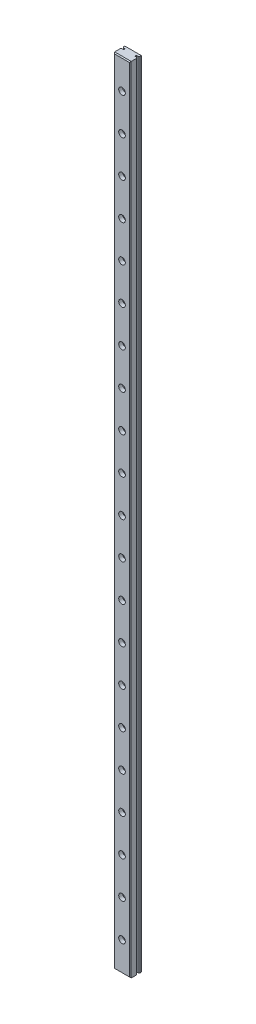
SolidWorks part; units mm, degrees
ref_plane "Alzado" through (0, 0, 0) normal (0, 0, 1) x (1, 0, 0)
ref_plane "Planta" through (0, 0, 0) normal (0, 1, 0) x (1, 0, 0)
ref_plane "Vista lateral" through (0, 0, 0) normal (1, 0, 0) x (0, 0, -1)
sketch "Croquis1" plane through (0, 0, 0) normal (0, 1, 0) x (1, 0, 0)
  line L1 (0, 0) -> (9, 0)
  line L2 (0, 0) -> (0, 6.5)
  line L3 (0, 6.5) -> (9, 6.5)
  line L4 (9, 0) -> (9, 6.5)
  dimension "D1" = 9
  dimension "D2" = 6.5
extrude "Saliente-Extruir1" add sketch "Croquis1" along normal blind 431
sketch "Croquis2" plane through (0, 431, 0) normal (0, 1, 0) x (1, 0, 0)
  line L0 (0, 4) -> (9, 4) construction
  line L1 (0, 6.5) -> (0, 0) construction
  line L2 (9, 0) -> (9, 6.5) construction
  line L3 (4.5, 6.5) -> (4.5, 0) construction
  line L4 (0, 4) -> (1.5, 4)
  line L5 (0, 4) -> (0, 4.75)
  line L6 (0, 4.75) -> (1.5, 4.75)
  line L7 (1.5, 4) -> (1.5, 4.75)
  line L8 (9, 6.5) -> (0, 6.5) construction
  line L9 (0, 0) -> (9, 0) construction
  line L10 (9, 4) -> (9, 4.75)
  line L11 (9, 4) -> (7.5, 4)
  line L12 (7.5, 4) -> (7.5, 4.75)
  line L13 (9, 4.75) -> (7.5, 4.75)
  dimension "D1" = 4
  dimension "D2" = 0.75
  dimension "D3" = 1.5
extrude "Cortar-Extruir1" cut sketch "Croquis2" against normal up to surface (431 mm away) up to face at (4.5, 0, -3.25)
chamfer "Chaflán2" distance 0.5 angle 45 4 edges at (9, 215.5, -4.75) (9, 215.5, -4) (0, 215.5, -4.75) (0, 215.5, -4)
sketch "Croquis3" plane through (0, 0, 0) normal (0, 0, 1) x (1, 0, 0)
  line L0 (4.5, 431) -> (4.5, 0) construction
  line L1 (0, 431) -> (9, 431) construction
  line L2 (0, 0) -> (9, 0) construction
  circle A0 centre (4.5, 415) radius 1.8
  circle A1 centre (4.5, 395) radius 1.8
  circle A2 centre (4.5, 375.0526) radius 1.8
  circle A3 centre (4.5, 355.1053) radius 1.8
  circle A4 centre (4.5, 335.1579) radius 1.8
  circle A5 centre (4.5, 315.2105) radius 1.8
  circle A6 centre (4.5, 295.2632) radius 1.8
  circle A7 centre (4.5, 275.3158) radius 1.8
  circle A8 centre (4.5, 255.3684) radius 1.8
  circle A9 centre (4.5, 235.4211) radius 1.8
  circle A10 centre (4.5, 215.4737) radius 1.8
  circle A11 centre (4.5, 195.5263) radius 1.8
  circle A12 centre (4.5, 175.5789) radius 1.8
  circle A13 centre (4.5, 155.6316) radius 1.8
  circle A14 centre (4.5, 135.6842) radius 1.8
  circle A15 centre (4.5, 115.7368) radius 1.8
  circle A16 centre (4.5, 95.7895) radius 1.8
  circle A17 centre (4.5, 75.8421) radius 1.8
  circle A18 centre (4.5, 55.8947) radius 1.8
  circle A19 centre (4.5, 35.9474) radius 1.8
  circle A20 centre (4.5, 16) radius 1.8
  dimension "D1" = 3.6
  dimension "D3" = 3.6
  dimension "D2" = 16
  dimension "D4" = 20
  dimension "D6" = 16
  dimension "D5" = 20
extrude "Cortar-Extruir2" cut sketch "Croquis3" against normal blind 440
chamfer "Chaflán4" distance 0.5 angle 45 8 edges at (4.5, 431, 0) (9, 215.5, 0) (0, 215.5, 0) (4.5, 0, 0) (4.5, 431, -6.5) (9, 215.5, -6.5) (4.5, 0, -6.5) (0, 215.5, -6.5)
sketch "Croquis4" plane through (0, 0, -6.5) normal (0, 0, -1) x (-1, 0, 0)
  circle A0 centre (-4.5, 415) radius 2.85
  circle A1 centre (-4.5, 395.05) radius 2.85
  circle A2 centre (-4.5, 375.1) radius 2.85
  circle A3 centre (-4.5, 355.15) radius 2.85
  circle A4 centre (-4.5, 335.2) radius 2.85
  circle A5 centre (-4.5, 315.25) radius 2.85
  circle A6 centre (-4.5, 295.3) radius 2.85
  circle A7 centre (-4.5, 275.35) radius 2.85
  circle A8 centre (-4.5, 255.4) radius 2.85
  circle A9 centre (-4.5, 235.45) radius 2.85
  circle A10 centre (-4.5, 215.5) radius 2.85
  circle A11 centre (-4.5, 195.55) radius 2.85
  circle A12 centre (-4.5, 175.6) radius 2.85
  circle A13 centre (-4.5, 155.65) radius 2.85
  circle A14 centre (-4.5, 135.7) radius 2.85
  circle A15 centre (-4.5, 115.75) radius 2.85
  circle A16 centre (-4.5, 95.8) radius 2.85
  circle A17 centre (-4.5, 75.85) radius 2.85
  circle A18 centre (-4.5, 55.9) radius 2.85
  circle A19 centre (-4.5, 35.95) radius 2.85
  circle A20 centre (-4.5, 16) radius 2.85
  dimension "D1" = 5.7
  dimension "D2" = 21
extrude "Cortar-Extruir3" cut sketch "Croquis4" against normal blind 4.4
